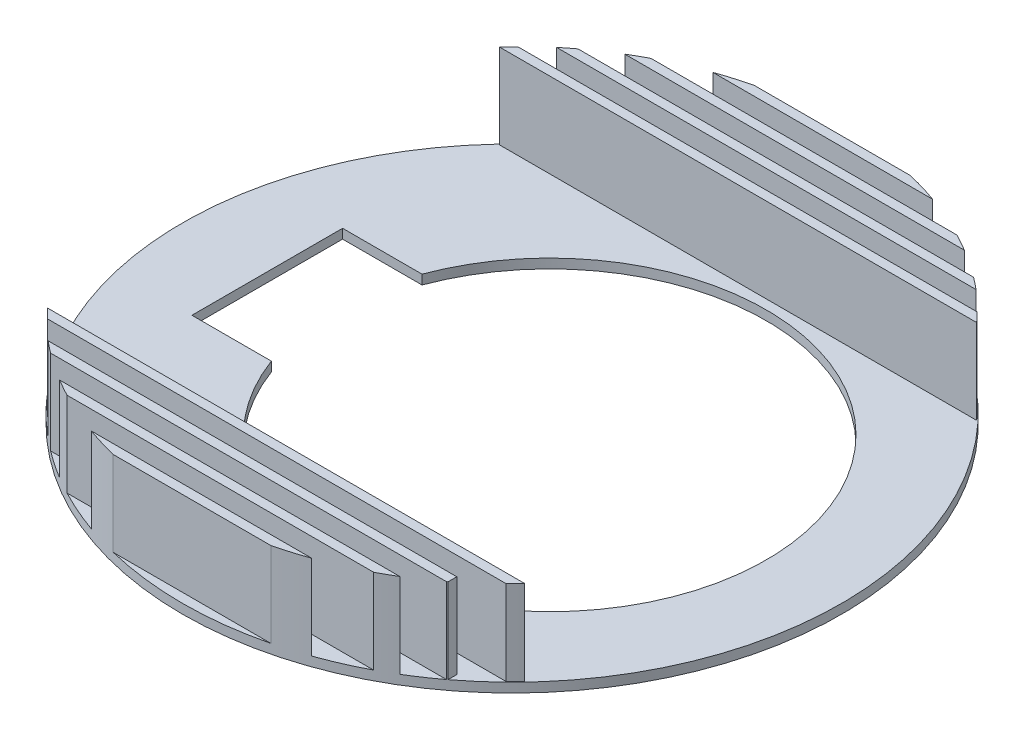
SolidWorks part; units mm, degrees
ref_plane "Front Plane" through (0, 0, 0) normal (0, 0, 1) x (1, 0, 0)
ref_plane "Top Plane" through (0, 0, 0) normal (0, 1, 0) x (1, 0, 0)
ref_plane "Right Plane" through (0, 0, 0) normal (1, 0, 0) x (0, 0, -1)
sketch "Sketch1" plane through (0, 0, 0) normal (0, 1, 0) x (1, 0, 0)
  circle A0 centre (0, 0) radius 17.5
extrude "Boss-Extrude1" add sketch "Sketch1" along normal blind 0.5
sketch "Sketch2" plane through (0, 0.5, 0) normal (0, 1, 0) x (1, 0, 0)
  circle A0 centre (2, 0) radius 11.5
extrude "Cut-Extrude1" cut sketch "Sketch2" against normal blind 0.5
sketch "Sketch3" plane through (0, 0, 0) normal (0, 1, 0) x (1, 0, 0)
  line L1 (2, 4) -> (-13, 4)
  line L2 (2, 4) -> (2, -4)
  line L3 (2, -4) -> (-13, -4)
  line L4 (-13, 4) -> (-13, -4)
extrude "Cut-Extrude4" cut sketch "Sketch3" along normal blind 2.5
sketch "Sketch4" plane through (0, 0, 0) normal (0, 1, 0) x (1, 0, 0)
  circle A0 centre (0, 0) radius 17.2585
  circle A1 centre (0, 0) radius 15.5
sketch "Sketch5" plane through (0, 0.5, 0) normal (0, 1, 0) x (1, 0, 0)
  circle A0 centre (0, 0) radius 14.5
  circle A1 centre (0, 0) radius 14.5
  circle A2 centre (0, 0) radius 14
sketch "Sketch6" plane through (0, 0.5, 0) normal (0, 1, 0) x (1, 0, 0)
  circle A0 centre (0, 0) radius 17.5
  circle A1 centre (0, 0) radius 17
sketch "Sketch7" plane through (0, 0.5, 0) normal (0, 1, 0) x (1, 0, 0)
  line L0 (0, 12.5) -> (0, 13.5)
  line L1 (0, 14) -> (0, 15)
  line L2 (0, 12) -> (12.6696, 12)
  line L3 (12.6696, 12) -> (0, 12)
  line L4 (-12.6696, 12) -> (0, 12)
  line L5 (0, -12) -> (12.6696, -12)
  line L6 (12.6696, -12) -> (0, -12)
  line L7 (0, -12) -> (-12.6696, -12)
  line L8 (0, 12.5) -> (-12.1765, 12.5)
  line L9 (0, -12.5) -> (-12.1765, -12.5)
  line L10 (0, -12.5) -> (12.1765, -12.5)
  line L11 (0, 12.5) -> (12.1765, 12.5)
  line L12 (-15.0094, 14) -> (0, 14)
  line L13 (-15.0094, 14) -> (-15.0094, 13.5)
  line L14 (-15.0094, 13.5) -> (0, 13.5)
  line L15 (0, 14) -> (0, 13.5)
  line L16 (12.6696, 13.5) -> (0, 13.5)
  line L17 (12.6696, 13.5) -> (12.6696, 14)
  line L18 (12.6696, 14) -> (0, 14)
  line L19 (0, 13.5) -> (0, 14)
  line L20 (0, 15.5) -> (0, 16.5)
  line L21 (0, 15) -> (-12.1765, 15)
  line L22 (0, 15) -> (0, 15.5)
  line L23 (0, 15.5) -> (-12.1765, 15.5)
  line L24 (-12.1765, 15) -> (-12.1765, 15.5)
  line L25 (10.5562, 15) -> (0, 15)
  line L26 (10.5562, 15) -> (10.5562, 15.5)
  line L27 (10.5562, 15.5) -> (0, 15.5)
  line L28 (0, 15) -> (0, 15.5)
  line L30 (0, 16.5) -> (-8.985, 16.5)
  line L31 (0, 16.5) -> (0, 17)
  line L32 (0, 17) -> (-8.985, 17)
  line L33 (-8.985, 16.5) -> (-8.985, 17)
  line L34 (9.7018, 17) -> (0, 17)
  line L35 (9.7018, 17) -> (9.7018, 16.5)
  line L36 (9.7018, 16.5) -> (0, 16.5)
  line L37 (0, 17) -> (0, 16.5)
  line L39 (-0.0002, -16.992) -> (12.6693, -16.992)
  line L40 (12.6693, -16.992) -> (-0.0002, -16.992)
  line L41 (-12.6698, -16.992) -> (-0.0002, -16.992)
  line L42 (-0.0002, -16.492) -> (-12.1768, -16.492)
  line L43 (-0.0002, -16.492) -> (12.1763, -16.492)
  line L44 (-15.0096, -14.992) -> (-0.0002, -14.992)
  line L45 (-15.0096, -14.992) -> (-15.0096, -15.492)
  line L46 (-15.0096, -15.492) -> (-0.0002, -15.492)
  line L47 (-0.0002, -14.992) -> (-0.0002, -15.492)
  line L48 (12.6693, -15.492) -> (-0.0002, -15.492)
  line L49 (12.6693, -15.492) -> (12.6693, -14.992)
  line L50 (12.6693, -14.992) -> (-0.0002, -14.992)
  line L51 (-0.0002, -15.492) -> (-0.0002, -14.992)
  line L53 (-0.0002, -13.992) -> (-12.1768, -13.992)
  line L54 (-0.0002, -13.992) -> (-0.0002, -13.492)
  line L55 (-0.0002, -13.492) -> (-12.1768, -13.492)
  line L56 (-12.1768, -13.992) -> (-12.1768, -13.492)
  line L57 (10.556, -13.992) -> (-0.0002, -13.992)
  line L58 (10.556, -13.992) -> (10.556, -13.492)
  line L59 (10.556, -13.492) -> (-0.0002, -13.492)
  line L60 (-0.0002, -13.992) -> (-0.0002, -13.492)
  arc A0 (12.1765, -12.5) -> (12.6696, -12) centre (0, 0) ccw
  arc A1 (12.1765, 12.5) -> (12.6696, 12) centre (0, 0) cw
  arc A2 (-12.1765, -12.5) -> (-12.6696, -12) centre (0, 0) cw
  arc A3 (-12.1765, 12.5) -> (-12.6696, 12) centre (0, 0) ccw
  arc A4 (12.1763, -16.492) -> (12.6693, -16.992) centre (-0.0002, -28.992) cw
  arc A5 (-12.1768, -16.492) -> (-12.6698, -16.992) centre (-0.0002, -28.992) ccw
  circle M10 centre (0, 0) radius 17.5
extrude "Boss-Extrude6" add sketch "Sketch7" along normal blind 4.5 contours A2 L9 L10 A0 L5 L7 | L54 L55 L53 M10 | L58 L59 L54 L57 M10 | L47 L44 L46 M10 | L50 L47 L48 M10 | L43 L42 L41 L39 M10 | L22 L23 L21 M10 | L27 L22 L25 M10 | L15 L12 L14 M10 | L18 L15 L16 M10 | L8 A3 L4 L2 A1 L11 | L31 L32 L30 M10 | L36 L34 L31 M10
